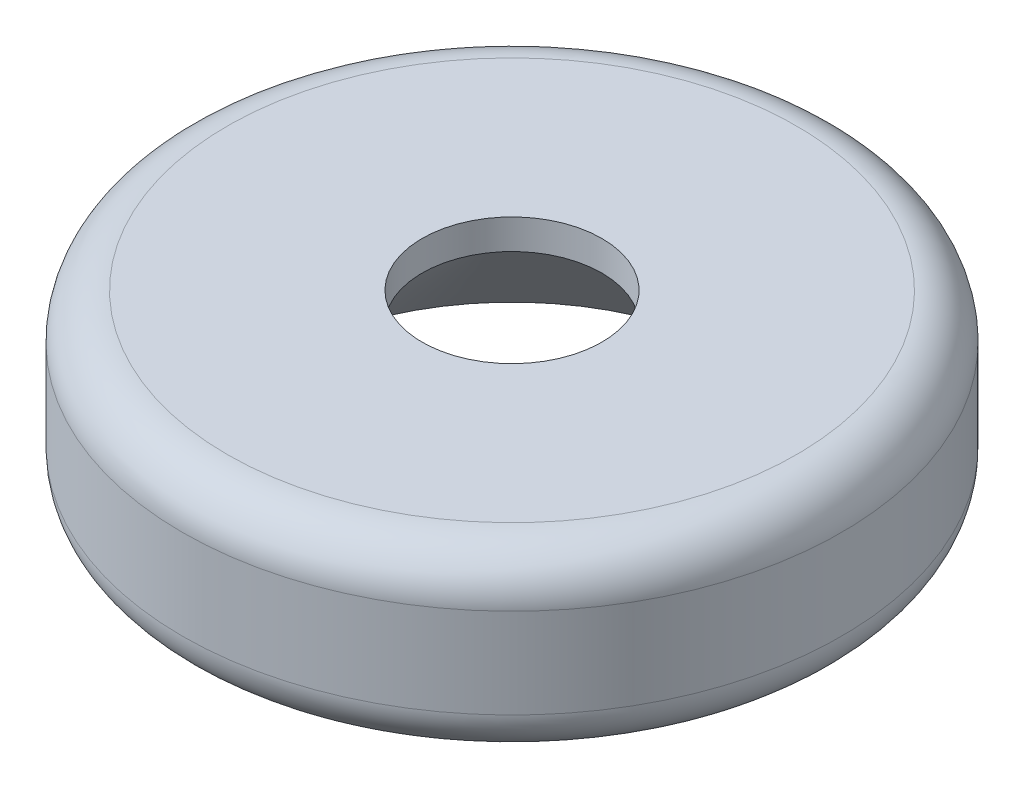
SolidWorks part; units mm, degrees
material "AISI 1020"
ref_plane "Plano superior" through (0, 0, 0) normal (0, 0, 1) x (1, 0, 0)
ref_plane "Plano frontal" through (0, 0, 0) normal (0, 1, 0) x (1, 0, 0)
ref_plane "Plano direito" through (0, 0, 0) normal (1, 0, 0) x (0, 0, -1)
sketch "Esboço1" plane through (0, 0, 0) normal (0, 1, 0) x (1, 0, 0)
  circle A0 centre (0, 0) radius 11
  dimension "D1" = 22
extrude "Ressalto-extrusão1" add sketch "Esboço1" along normal blind 6
sketch "Esboço10" plane through (0, 0, 0) normal (0, -1, 0) x (1, 0, 0)
  circle A0 centre (0, 0) radius 8
  dimension "D1" = 16
extrude "Corte-extrusão4" cut sketch "Esboço10" against normal blind 5 draft 45
sketch "Esboço11" plane through (0, 5, 0) normal (0, -1, 0) x (1, 0, 0)
  circle A0 centre (0, 0) radius 3
  dimension "D1" = 6
extrude "Corte-extrusão5" cut sketch "Esboço11" against normal through all
fillet "Filete4" radius 1.5 1 edges at (0, 0, 11)
fillet "Filete5" radius 1.5 1 edges at (0, 6, 11)
